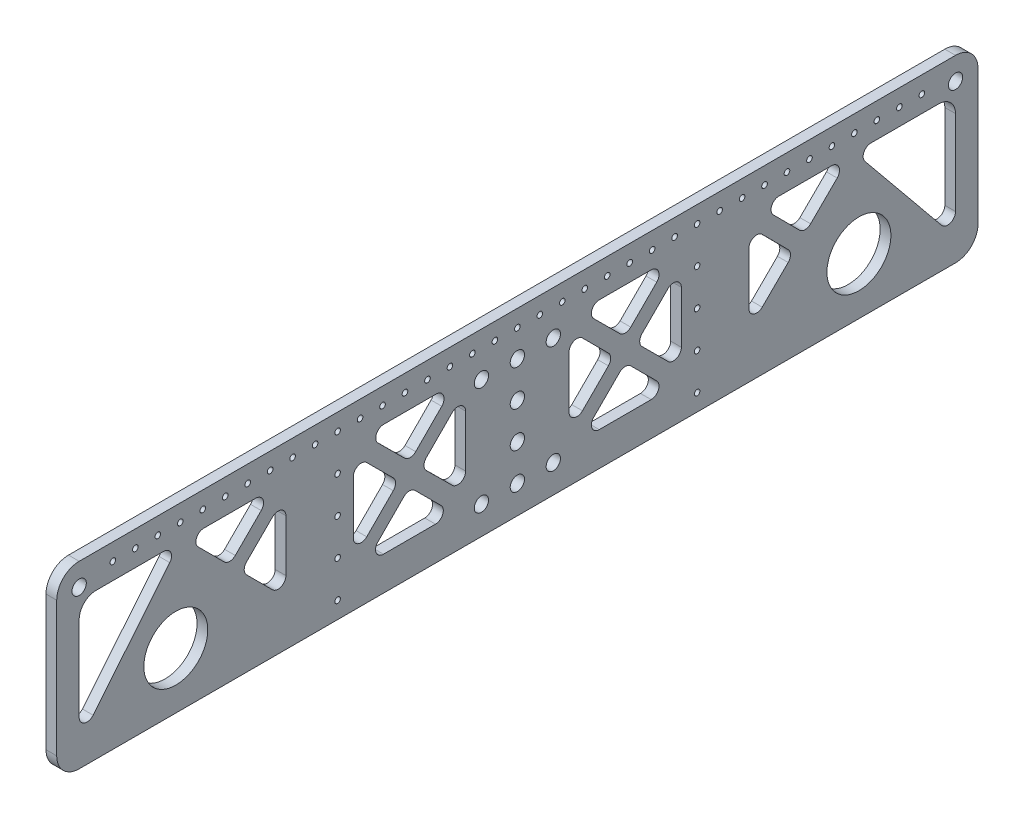
SolidWorks part; units mm, degrees
material "6061 Alloy"
ref_plane "Front Plane" through (0, 0, 0) normal (0, 0, 1) x (1, 0, 0)
ref_plane "Top Plane" through (0, 0, 0) normal (0, 1, 0) x (1, 0, 0)
ref_plane "Right Plane" through (0, 0, 0) normal (1, 0, 0) x (0, 0, -1)
sketch "Sketch2" plane through (0, 0, 0) normal (1, 0, 0) x (0, 0, -1)
  line L0 (-23.4813, 28.6683) -> (-23.4813, -31.3317)
  line L1 (-13.4813, 38.6683) -> (376.5187, 38.6683)
  line L2 (-13.4813, -41.3317) -> (376.5187, -41.3317)
  line L3 (386.5187, 28.6683) -> (386.5187, -31.3317)
  line L4 (108.5187, -13.4215) -> (108.5187, 10.2468)
  line L9 (121.9261, -26.3034) -> (145.0689, -26.3034)
  line L10 (122.0111, 23.6966) -> (145.3987, 23.6966)
  line L11 (158.5187, -12.5773) -> (158.5187, 10.5251)
  line L12 (204.5187, 10.2486) -> (204.5187, -12.8519)
  line L13 (217.9684, 23.6983) -> (241.0689, 23.6983)
  line L14 (217.9684, -26.3017) -> (241.0689, -26.3017)
  line L15 (114.4935, 12.7217) -> (126.2857, 0.9296)
  line L16 (254.5187, 10.2486) -> (254.5187, -12.8519)
  line L17 (119.545, 17.7129) -> (131.3219, 6.0194)
  line L18 (227.0438, -8.7766) -> (215.4935, -20.3268)
  line L19 (119.4425, -20.3374) -> (130.9728, -8.7249)
  line L20 (231.9935, 6.1732) -> (243.5438, 17.7234)
  line L21 (147.8824, 17.7305) -> (136.2716, 6.037)
  line L22 (135.9313, -8.7161) -> (147.5438, -20.3286)
  line L23 (141.0017, -3.5918) -> (152.5526, -15.061)
  line L24 (140.9841, 1.3579) -> (152.535, 12.9912)
  line L25 (126.2945, -4.0114) -> (114.5023, -15.8876)
  line L26 (78.5187, 10.2468) -> (78.5187, -12.8537)
  line L27 (248.5438, 12.7234) -> (236.9935, 1.1732)
  line L28 (210.4935, -15.3268) -> (222.0438, -3.7766)
  line L29 (231.9935, -8.7766) -> (243.5438, -20.3268)
  line L30 (210.4935, 12.7234) -> (222.0438, 1.1732)
  line L31 (227.0438, 6.1732) -> (215.4935, 17.7234)
  line L32 (248.5438, -15.3268) -> (236.9935, -3.7766)
  line L33 (65.0689, 23.6966) -> (41.9684, 23.6966)
  line L36 (284.5187, 10.2005) -> (284.5187, -12.8995)
  line L37 (297.9208, 23.6983) -> (321.3825, 23.6983)
  line L38 (51.0438, 6.1714) -> (39.4935, 17.7217)
  line L40 (72.5438, -15.3286) -> (60.9935, -3.7783)
  line L45 (72.5438, 12.7217) -> (60.9935, 1.1714)
  line L46 (67.5438, 17.7217) -> (55.9935, 6.1714)
  line L48 (323.8475, 17.7135) -> (312.0227, 5.9831)
  line L51 (376.5187, -21.5226) -> (376.5187, 16.1983)
  line L52 (369.0187, 23.6983) -> (338.902, 23.6983)
  line L53 (295.4361, 17.7334) -> (307.073, 6.0029)
  line L54 (290.5034, 12.6654) -> (302.0531, 1.023)
  line L55 (302.0333, -3.9267) -> (290.4836, -15.3843)
  line L56 (336.1925, 17.9827) -> (370.3092, -23.7382)
  line L57 (-7.2719, -23.7385) -> (26.8446, 17.9809)
  line L58 (24.1352, 23.6966) -> (-5.9813, 23.6966)
  line L59 (-13.4813, 16.1966) -> (-13.4813, -21.5229)
  circle A1 centre (29.5187, -16.3317) radius 14.225
  circle A2 centre (333.5187, -16.3317) radius 14.225
  arc A15 (-23.4813, 28.6683) -> (-13.4813, 38.6683) centre (-13.4813, 28.6683) cw
  arc A16 (-13.4813, -41.3317) -> (-23.4813, -31.3317) centre (-13.4813, -31.3317) cw
  arc A17 (386.5187, 28.6683) -> (376.5187, 38.6683) centre (376.5187, 28.6683) ccw
  arc A18 (376.5187, -41.3317) -> (386.5187, -31.3317) centre (376.5187, -31.3317) ccw
  circle A59 centre (181.5187, -28.7717) radius 3.18
  circle A60 centre (197.5187, -28.7717) radius 3.18
  circle A63 centre (197.5187, 19.2283) radius 3.18
  circle A64 centre (181.5187, -12.7717) radius 3.18
  circle A65 centre (181.5187, 3.2283) radius 3.18
  circle A66 centre (181.5187, 19.2283) radius 3.18
  circle A67 centre (165.5187, -28.7717) radius 3.18
  circle A68 centre (165.5187, 19.2283) radius 3.18
  circle A69 centre (197.5187, -12.7717) radius 3.18 [skipped]
  circle A70 centre (197.5187, 3.2283) radius 3.18 [skipped]
  circle A71 centre (-8.4813, 31.1683) radius 1.25 construction
  circle A152 centre (1.5187, 31.1683) radius 1.25
  circle A153 centre (11.5187, 31.1683) radius 1.25
  circle A154 centre (21.5187, 31.1683) radius 1.25
  circle A155 centre (31.5187, 31.1683) radius 1.25
  circle A156 centre (41.5187, 31.1683) radius 1.25
  circle A157 centre (51.5187, 31.1683) radius 1.25
  circle A158 centre (61.5187, 31.1683) radius 1.25
  circle A159 centre (71.5187, 31.1683) radius 1.25
  circle A160 centre (81.5187, 31.1683) radius 1.25
  circle A161 centre (91.5187, 31.1683) radius 1.25
  circle A162 centre (101.5187, 31.1683) radius 1.25
  circle A163 centre (111.5187, 31.1683) radius 1.25
  circle A164 centre (121.5187, 31.1683) radius 1.25
  circle A165 centre (131.5187, 31.1683) radius 1.25
  circle A166 centre (141.5187, 31.1683) radius 1.25
  circle A167 centre (151.5187, 31.1683) radius 1.25
  circle A168 centre (161.5187, 31.1683) radius 1.25
  circle A169 centre (171.5187, 31.1683) radius 1.25
  circle A170 centre (181.5187, 31.1683) radius 1.25
  circle A171 centre (191.5187, 31.1683) radius 1.25
  circle A172 centre (201.5187, 31.1683) radius 1.25
  circle A173 centre (211.5187, 31.1683) radius 1.25
  circle A174 centre (221.5187, 31.1683) radius 1.25
  circle A175 centre (231.5187, 31.1683) radius 1.25
  circle A176 centre (241.5187, 31.1683) radius 1.25
  circle A177 centre (251.5187, 31.1683) radius 1.25
  circle A178 centre (261.5187, 31.1683) radius 1.25
  circle A179 centre (271.5187, 31.1683) radius 1.25
  circle A180 centre (281.5187, 31.1683) radius 1.25
  circle A181 centre (291.5187, 31.1683) radius 1.25
  circle A182 centre (301.5187, 31.1683) radius 1.25
  circle A183 centre (311.5187, 31.1683) radius 1.25
  circle A184 centre (321.5187, 31.1683) radius 1.25
  circle A185 centre (331.5187, 31.1683) radius 1.25
  circle A186 centre (341.5187, 31.1683) radius 1.25
  circle A187 centre (351.5187, 31.1683) radius 1.25
  circle A188 centre (361.5187, 31.1683) radius 1.25
  circle A200 centre (101.5187, -33.8317) radius 1.25
  circle A216 centre (261.5187, -33.8317) radius 1.25
  circle A229 centre (181.5187, -33.8317) radius 1.25 [skipped]
  circle A230 centre (201.5187, -33.8317) radius 1.25 [skipped]
  circle A231 centre (161.5187, -33.8317) radius 1.25 [skipped]
  circle A232 centre (151.5187, -33.8317) radius 1.25 [skipped]
  circle A233 centre (141.5187, -33.8317) radius 1.25 [skipped]
  circle A234 centre (131.5187, -33.8317) radius 1.25 [skipped]
  circle A235 centre (171.5187, -33.8317) radius 1.25 [skipped]
  circle A236 centre (191.5187, -33.8317) radius 1.25 [skipped]
  circle A237 centre (211.5187, -33.8317) radius 1.25 [skipped]
  circle A238 centre (221.5187, -33.8317) radius 1.25 [skipped]
  circle A239 centre (231.5187, -33.8317) radius 1.25 [skipped]
  circle A240 centre (31.5187, -33.8317) radius 1.25 [skipped]
  circle A241 centre (21.5187, -33.8317) radius 1.25 [skipped]
  circle A242 centre (331.5187, -33.8317) radius 1.25 [skipped]
  circle A243 centre (341.5187, -33.8317) radius 1.25 [skipped]
  circle A245 centre (-13.4813, 28.6683) radius 3.18
  circle A247 centre (376.5187, 28.6683) radius 3.18
  circle A248 centre (371.5187, 31.1683) radius 1.25 [skipped]
  circle A249 centre (371.5187, -33.8317) radius 1.25 [skipped]
  circle A250 centre (-8.4813, -33.8317) radius 1.25 [skipped]
  circle A257 centre (121.5187, -33.8317) radius 1.25 [skipped]
  circle A267 centre (101.5187, -17.5817) radius 1.25
  circle A268 centre (261.5187, -17.5817) radius 1.25
  circle A269 centre (101.5187, -1.3317) radius 1.25
  circle A270 centre (261.5187, -1.3317) radius 1.25
  circle A271 centre (101.5187, 14.9183) radius 1.25
  circle A272 centre (261.5187, 14.9183) radius 1.25
  arc A273 (323.8475, 17.7135) -> (321.3825, 23.6983) centre (321.3825, 20.1983) ccw
  arc A274 (297.9208, 23.6983) -> (295.4361, 17.7334) centre (297.9208, 20.1983) ccw
  arc A275 (307.073, 6.0029) -> (312.0227, 5.9831) centre (309.5578, 8.4678) ccw
  arc A276 (290.4836, -15.3843) -> (284.5187, -12.8995) centre (288.0187, -12.8995) cw
  arc A277 (290.5034, 12.6654) -> (284.5187, 10.2005) centre (288.0187, 10.2005) ccw
  arc A278 (302.0531, 1.023) -> (302.0333, -3.9267) centre (299.5683, -1.442) cw
  arc A279 (215.4935, 17.7234) -> (217.9684, 23.6983) centre (217.9684, 20.1983) cw
  arc A280 (241.0689, 23.6983) -> (243.5438, 17.7234) centre (241.0689, 20.1983) cw
  arc A281 (254.5187, 10.2486) -> (248.5438, 12.7234) centre (251.0187, 10.2486) ccw
  arc A282 (254.5187, -12.8519) -> (248.5438, -15.3268) centre (251.0187, -12.8519) cw
  arc A283 (243.5438, -20.3268) -> (241.0689, -26.3017) centre (241.0689, -22.8017) cw
  arc A284 (217.9684, -26.3017) -> (215.4935, -20.3268) centre (217.9684, -22.8017) cw
  arc A285 (227.0438, -8.7766) -> (231.9935, -8.7766) centre (229.5187, -11.2514) cw
  arc A286 (236.9935, 1.1732) -> (236.9935, -3.7766) centre (239.4684, -1.3017) ccw
  arc A287 (231.9935, 6.1732) -> (227.0438, 6.1732) centre (229.5187, 8.6481) cw
  arc A288 (222.0438, -3.7766) -> (222.0438, 1.1732) centre (219.5689, -1.3017) ccw
  arc A289 (204.5187, -12.8519) -> (210.4935, -15.3268) centre (208.0187, -12.8519) ccw
  arc A290 (204.5187, 10.2486) -> (210.4935, 12.7234) centre (208.0187, 10.2486) cw
  arc A291 (147.5438, -20.3286) -> (145.0689, -26.3034) centre (145.0689, -22.8034) cw
  arc A292 (152.5526, -15.061) -> (158.5187, -12.5773) centre (155.0187, -12.5773) ccw
  arc A293 (152.535, 12.9912) -> (158.5187, 10.5251) centre (155.0187, 10.5251) cw
  arc A294 (145.3987, 23.6966) -> (147.8824, 17.7305) centre (145.3987, 20.1966) cw
  arc A295 (122.0111, 23.6966) -> (119.545, 17.7129) centre (122.0111, 20.1966) ccw
  arc A296 (108.5187, 10.2468) -> (114.4935, 12.7217) centre (112.0187, 10.2468) cw
  arc A297 (135.9313, -8.7161) -> (130.9728, -8.7249) centre (133.4564, -11.1909) ccw
  arc A298 (141.0017, -3.5918) -> (140.9841, 1.3579) centre (143.4678, -1.1082) cw
  arc A299 (131.3219, 6.0194) -> (136.2716, 6.037) centre (133.788, 8.503) ccw
  arc A300 (126.2857, 0.9296) -> (126.2945, -4.0114) centre (123.8108, -1.5453) cw
  arc A301 (108.5187, -13.4215) -> (114.5023, -15.8876) centre (112.0187, -13.4215) ccw
  arc A302 (121.9261, -26.3034) -> (119.4425, -20.3374) centre (121.9261, -22.8034) cw
  arc A303 (78.5187, -12.8537) -> (72.5438, -15.3286) centre (75.0187, -12.8537) cw
  arc A304 (60.9935, 1.1714) -> (60.9935, -3.7783) centre (63.4684, -1.3034) ccw
  arc A305 (78.5187, 10.2468) -> (72.5438, 12.7217) centre (75.0187, 10.2468) ccw
  arc A306 (55.9935, 6.1714) -> (51.0438, 6.1714) centre (53.5187, 8.6463) cw
  arc A307 (67.5438, 17.7217) -> (65.0689, 23.6966) centre (65.0689, 20.1966) ccw
  arc A308 (39.4935, 17.7217) -> (41.9684, 23.6966) centre (41.9684, 20.1966) cw
  arc A315 (338.902, 23.6983) -> (336.1925, 17.9827) centre (338.902, 20.1983) ccw
  arc A317 (376.5187, -21.5226) -> (370.3092, -23.7382) centre (373.0187, -21.5226) cw
  arc A318 (26.8446, 17.9809) -> (24.1352, 23.6966) centre (24.1352, 20.1966) ccw
  arc A319 (-7.2719, -23.7385) -> (-13.4813, -21.5229) centre (-9.9813, -21.5229) cw
  arc A321 (-5.9813, 23.6966) -> (-13.4813, 16.1966) centre (-5.9813, 16.1966) ccw
  arc A322 (369.0187, 23.6983) -> (376.5187, 16.1983) centre (369.0187, 16.1983) cw
  circle A323 centre (11.5187, -33.8317) radius 1.25 [skipped]
  circle A324 centre (1.5187, -33.8317) radius 1.25 [skipped]
  circle A325 centre (41.5187, -33.8317) radius 1.25 [skipped]
  circle A326 centre (51.5187, -33.8317) radius 1.25 [skipped]
  circle A327 centre (61.5187, -33.8317) radius 1.25 [skipped]
  circle A328 centre (81.5187, -33.8317) radius 1.25 [skipped]
  circle A329 centre (111.5187, -33.8317) radius 1.25 [skipped]
  circle A330 centre (91.5187, -33.8317) radius 1.25 [skipped]
  circle A331 centre (71.5187, -33.8317) radius 1.25 [skipped]
  circle A332 centre (321.5187, -33.8317) radius 1.25 [skipped]
  circle A333 centre (311.5187, -33.8317) radius 1.25 [skipped]
  circle A334 centre (301.5187, -33.8317) radius 1.25 [skipped]
  circle A335 centre (291.5187, -33.8317) radius 1.25 [skipped]
  circle A336 centre (281.5187, -33.8317) radius 1.25 [skipped]
  circle A337 centre (271.5187, -33.8317) radius 1.25 [skipped]
  circle A338 centre (251.5187, -33.8317) radius 1.25 [skipped]
  circle A339 centre (241.5187, -33.8317) radius 1.25 [skipped]
  circle A340 centre (361.5187, -33.8317) radius 1.25 [skipped]
  circle A341 centre (351.5187, -33.8317) radius 1.25 [skipped]
  point P32 (-23.4813, 38.6683)
  point P35 (-23.4813, -41.3317)
  point P40 (386.5187, -41.3317)
  point P123 (181.5187, -41.3317)
  point P220 (304.518, -1.4618)
  point P273 (229.5187, -6.3017)
  point P278 (229.5187, 3.6983)
  point P301 (138.518, -1.1258)
  point P306 (128.7518, -1.5365)
  point P319 (53.5187, 3.6966)
  dimension "D3" = 25
  dimension "D7" = 10
  dimension "D8" = 10
  dimension "D9" = 10
  dimension "D10" = 10
  dimension "D11" = 7.5
  dimension "D13" = 12.56
  dimension "D20" = 4
  dimension "D23" = 3.5
  dimension "D21" = 3.5
  dimension "D26" = 7.5
  dimension "D31" = 7.5
  dimension "D1" = 80
  dimension "D2" = 410
  dimension "D4" = 53
  dimension "D5" = 25
  dimension "D6" = 53
  dimension "D12" = 15
  dimension "D14" = 205
  dimension "D22" = 6.6409
  dimension "D24" = 132
  dimension "D25" = 30
  dimension "D27" = 132
  dimension "D28" = 15.0283
  dimension "D29" = 15.03
  dimension "D30" = 49
  dimension "D15" = 2
  dimension "D16" = 4
  dimension "D17" = 2
  dimension "D18" = 39
  dimension "D19" = 2
extrude "Boss-Extrude1" add sketch "Sketch2" along normal blind 4.7625
